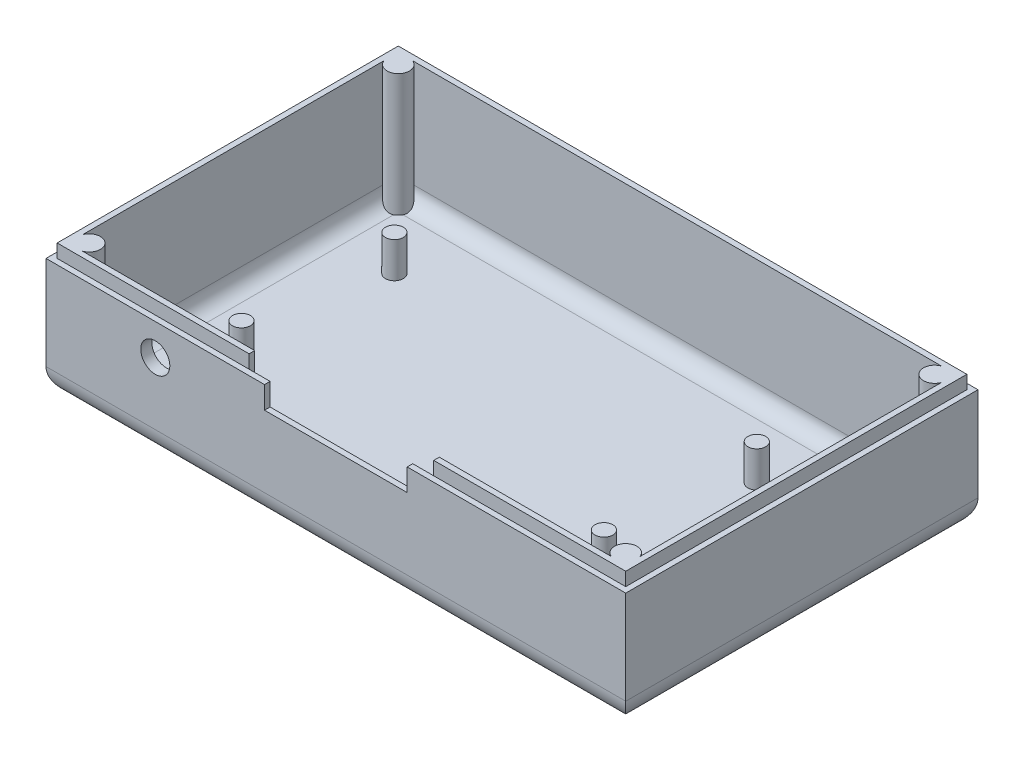
SolidWorks part; units mm, degrees
ref_plane "Front Plane" through (0, 0, 0) normal (0, 0, 1) x (1, 0, 0)
ref_plane "Top Plane" through (0, 0, 0) normal (0, 1, 0) x (1, 0, 0)
ref_plane "Right Plane" through (0, 0, 0) normal (1, 0, 0) x (0, 0, -1)
sketch "Sketch1" plane through (0, 0, 0) normal (0, 1, 0) x (1, 0, 0)
  line L1 (-65, -39.5) -> (65, -39.5)
  line L2 (-65, -39.5) -> (-65, 39.5)
  line L3 (-65, 39.5) -> (65, 39.5)
  line L4 (65, -39.5) -> (65, 39.5)
  line L5 (-65, -39.5) -> (65, 39.5) construction
  line L6 (-65, 39.5) -> (65, -39.5) construction
  point P0 (0, 0)
  dimension "D1" = 130
  dimension "D2" = 79
extrude "Boss-Extrude1" add sketch "Sketch1" along normal blind 30
fillet "Fillet1" radius 6 4 edges at (-65, 0, 0) (0, 0, -39.5) (65, 0, 0) (0, 0, 39.5)
shell "Shell1" thickness 2.5
sketch "Sketch2" plane through (0, 30, 0) normal (0, 1, 0) x (1, 0, 0)
  line L8 (63.75, -38.25) -> (63.75, 38.25)
  line L9 (63.75, 38.25) -> (-63.75, 38.25)
  line L10 (-63.75, 38.25) -> (-63.75, -38.25)
  line L11 (-63.75, -38.25) -> (63.75, -38.25)
  line L12 (63.75, -38.25) -> (63.75, 38.25)
  line L13 (63.75, 38.25) -> (-63.75, 38.25)
  line L14 (-63.75, 38.25) -> (-63.75, -38.25)
  line L15 (-63.75, -38.25) -> (63.75, -38.25)
  line L20 (65, -39.5) -> (65, 39.5)
  line L21 (65, 39.5) -> (-65, 39.5)
  line L22 (-65, 39.5) -> (-65, -39.5)
  line L23 (-65, -39.5) -> (65, -39.5)
  line L24 (65, -39.5) -> (65, 39.5)
  line L25 (65, 39.5) -> (-65, 39.5)
  line L26 (-65, 39.5) -> (-65, -39.5)
  line L27 (-65, -39.5) -> (65, -39.5)
  dimension "D1" = 1.25
  dimension "D2" = 0
extrude "Cut-Extrude1" cut sketch "Sketch2" against normal blind 3
sketch "Sketch3" plane through (0, 2.5, 0) normal (0, 1, 0) x (1, 0, 0)
  circle A0 centre (-47.5038, 21.1226) radius 2
  circle A1 centre (33.7762, 21.1226) radius 2
  circle A2 centre (-47.5038, -13.1674) radius 2
  circle A3 centre (33.7762, -13.1674) radius 2
  dimension "D3" = 4
  dimension "D1" = 81.28
  dimension "D2" = 34.29
extrude "Boss-Extrude2" add sketch "Sketch3" along normal blind 8
sketch "Sketch4" plane through (0, 30, 0) normal (0, 1, 0) x (1, 0, 0)
  line L0 (0, 39.5) -> (0, -39.5) construction
  line L1 (65, 39.5) -> (-65, 39.5) construction
  line L2 (-65, -39.5) -> (65, -39.5) construction
  line L3 (-65, 0) -> (65, 0) construction
  line L4 (-65, 39.5) -> (-65, -39.5) construction
  line L5 (65, -39.5) -> (65, 39.5) construction
  line L6 (62.5, 37) -> (-62.5, 37) construction
  line L9 (-62.5, 37) -> (-62.5, -37) construction
  line L10 (-62.5, 37) -> (-62.5, 35.5029)
  line L11 (-62.5, 37) -> (-62.5, -37) construction
  line L12 (-62.5, 37) -> (-61.0029, 37)
  line L19 (62.5, 37) -> (62.5, 35.5029)
  line L20 (62.5, 37) -> (61.0029, 37)
  line L21 (-62.5, -37) -> (-62.5, -35.5029)
  line L22 (-62.5, -37) -> (-61.0029, -37)
  line L23 (62.5, -37) -> (61.0029, -37)
  line L24 (62.5, -37) -> (62.5, -35.5029)
  arc A1 (-62.5, 35.5029) -> (-61.0029, 37) centre (-60.15, 34.65) ccw
  arc A19 (62.5, 35.5029) -> (61.0029, 37) centre (60.15, 34.65) cw
  arc A20 (-62.5, -35.5029) -> (-61.0029, -37) centre (-60.15, -34.65) cw
  arc A21 (62.5, -35.5029) -> (61.0029, -37) centre (60.15, -34.65) ccw
  dimension "D1" = 5
  dimension "D2" = 2.35
  dimension "D3" = 2.35
extrude "Boss-Extrude3" add sketch "Sketch4" against normal up to body separate body
ref_plane "Plane1" through (0, 20, 0) normal (0, 1, 0) x (1, 0, 0)
sketch "Sketch5" plane through (0, 0, 39.5) normal (0, 0, 1) x (1, 0, 0)
  line L0 (-63.75, 30) -> (63.75, 30) construction
  line L1 (-15.99, 30) -> (15.99, 30)
  line L2 (-15.99, 30) -> (-15.99, 22.02)
  line L3 (-15.99, 22.02) -> (15.99, 22.02)
  line L4 (15.99, 30) -> (15.99, 22.02)
  line L5 (-15.99, 30) -> (15.99, 22.02) construction
  line L6 (-15.99, 22.02) -> (15.99, 30) construction
  point P0 (0, 26.01)
  point P5 (0, 0)
  dimension "D1" = 7.98
  dimension "D2" = 31.98
extrude "Cut-Extrude2" cut sketch "Sketch5" against normal up to surface (2.5 mm away) up to face at (0, 18, 37)
sketch "Sketch6" plane through (0, 0, 37) normal (0, 0, -1) x (-1, 0, 0)
  line L1 (20.7, 34.81) -> (-20.7, 34.81)
  line L2 (20.7, 34.81) -> (20.7, 10.51)
  line L3 (20.7, 10.51) -> (-20.7, 10.51)
  line L4 (-20.7, 34.81) -> (-20.7, 10.51)
  line L5 (20.7, 34.81) -> (-20.7, 10.51) construction
  line L6 (20.7, 10.51) -> (-20.7, 34.81) construction
  line L7 (15.99, 22.02) -> (-15.99, 22.02) construction
  point P0 (0, 22.66)
  point P5 (0, 0)
  point P7 (0, 16.093)
  dimension "D1" = 41.4
  dimension "D2" = 24.3
  dimension "D3" = 11.51
extrude "Cut-Extrude3" cut sketch "Sketch6" against normal blind 1.25
sketch "Sketch7" plane through (0, 0, 39.5) normal (0, 0, 1) x (1, 0, 0)
  line L0 (-65, 27) -> (-15.99, 27) construction
  line L2 (42.075, 20) -> (-42.075, 20) construction
  circle A0 centre (-40.495, 20) radius 3.26
  point P4 (-40.495, 27)
  point P5 (0, 0)
  dimension "D1" = 6.52
extrude "Cut-Extrude4" cut sketch "Sketch7" against normal up to next
